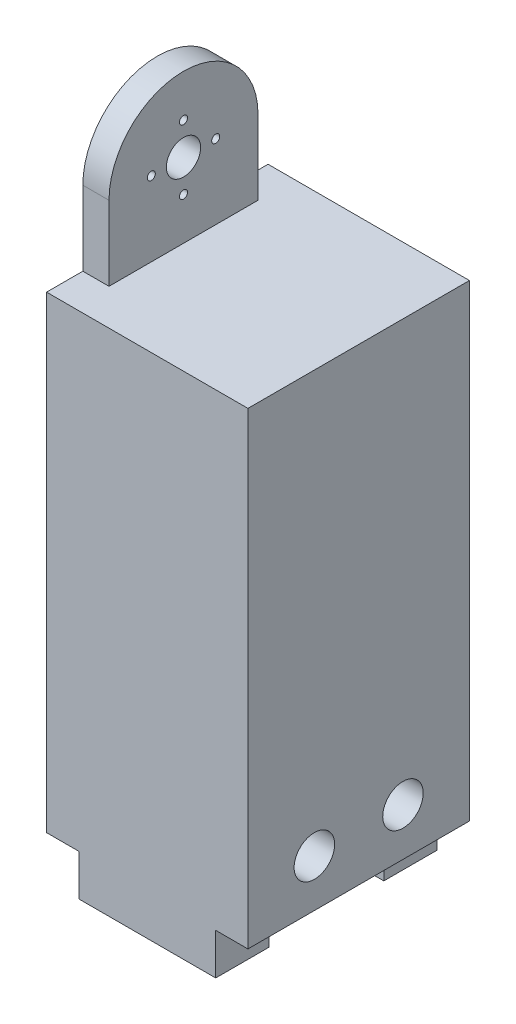
SolidWorks part; units mm, degrees
ref_plane "Front Plane" through (0, 0, 0) normal (0, 0, 1) x (1, 0, 0)
ref_plane "Top Plane" through (0, 0, 0) normal (0, 1, 0) x (1, 0, 0)
ref_plane "Right Plane" through (0, 0, 0) normal (1, 0, 0) x (0, 0, -1)
sketch "Sketch1" plane through (0, 0, 0) normal (0, 0, 1) x (1, 0, 0)
  line L1 (-25, 0) -> (25, 0)
  line L2 (-25, 0) -> (-25, -150)
  line L3 (-25, -150) -> (25, -150)
  line L4 (25, 0) -> (25, -150)
  dimension "D1" = 50
  dimension "D2" = 150
extrude "Boss-Extrude1" add sketch "Sketch1" against normal blind 55
sketch "Sketch2" plane through (25, 0, 0) normal (1, 0, 0) x (0, 0, -1)
  line L0 (55, 0) -> (0, 0) construction
  line L1 (0, -150) -> (0, 0) construction
  circle A0 centre (27.5, -25) radius 10.25
  dimension "D1" = 25
  dimension "D2" = 27.5
extrude "Cut-Extrude1" cut sketch "Sketch2" against normal blind 45 and the other way through all
sketch "Sketch7" plane through (-20, 0, 0) normal (1, 0, 0) x (0, 0, -1)
  line L0 (27.5, -17) -> (27.5, -33) construction
  circle A0 centre (27.5, -25) radius 8
  circle A1 centre (27.5, -17) radius 1
  circle A2 centre (35.5, -25) radius 1
  circle A3 centre (27.5, -33) radius 1
  circle A4 centre (19.5, -25) radius 1
  circle A5 centre (27.5, -25) radius 4.25
  point P14 (27.5, -25)
  dimension "D1" = 16
  dimension "D2" = 2
  dimension "D4" = 8.5
  dimension "D3" = 4
extrude "Cut-Extrude3" cut sketch "Sketch7" against normal blind 10 contours L0 A0 A1 | A0 A1 | A0 L0 A1 | A0 A4 | A0 A4 | L0 A3 A0 | A3 L0 A0 | A0 A3 | A0 A2 | A0 A2 | A5 L0 | L0 A5
sketch "Sketch8" plane through (25, 0, 0) normal (1, 0, 0) x (0, 0, -1)
  line L1 (55, -150) -> (55, 0) construction
  line L3 (0, -150) -> (55, -150)
  line L4 (0, -150) -> (0, -205)
  line L5 (0, -205) -> (55, -205)
  line L6 (55, -150) -> (55, -205)
  circle A1 centre (27.5, -180) radius 10.25
  circle A3 centre (27.5, -25) radius 10.25 construction
  dimension "D1" = 27.5
  dimension "D2" = 155
  dimension "D3" = 25
extrude "Boss-Extrude2" add sketch "Sketch8" against normal blind 50
sketch "Sketch10" plane through (0, 0, 0) normal (0, 0, 1) x (1, 0, 0)
  line L0 (-25, -205) -> (25, -205) construction
  line L5 (17, -205) -> (-17, -205)
  line L6 (17, -205) -> (17, -144.75)
  line L8 (-17, -205) -> (-17, -144.75)
  line L9 (-25, 0) -> (-25, -205) construction
  line L10 (-25, -180) -> (25, -180)
  line L13 (25, -169.75) -> (-25, -169.75)
  line L14 (25, -169.75) -> (25, -190.25)
  line L15 (25, -190.25) -> (-25, -190.25)
  line L16 (-25, -169.75) -> (-25, -190.25)
  line L17 (25, -205) -> (25, 0) construction
  line L18 (0, -180) -> (17, -180)
  line L19 (0, -180) -> (0, -191.25)
  line L20 (0, -191.25) -> (17, -191.25)
  line L21 (17, -180) -> (17, -191.25)
  line L22 (17, -191.25) -> (-17, -191.25)
  line L23 (17, -191.25) -> (17, -169.75)
  line L24 (17, -169.75) -> (-17, -169.75)
  line L25 (-17, -191.25) -> (-17, -169.75)
  line L26 (17, -191.25) -> (-17, -191.25)
  line L27 (17, -191.25) -> (17, -144.75)
  line L28 (17, -144.75) -> (-17, -144.75)
  line L29 (-17, -191.25) -> (-17, -144.75)
  line L30 (-25, -169.75) -> (-17, -169.75)
  line L31 (-25, -169.75) -> (-25, -205)
  line L32 (-25, -205) -> (-17, -205)
  line L33 (-17, -169.75) -> (-17, -205)
  line L34 (25, -169.75) -> (17, -169.75)
  line L35 (25, -169.75) -> (25, -205)
  line L36 (25, -205) -> (17, -205)
  line L37 (17, -169.75) -> (17, -205)
  line L38 (-25, -169.75) -> (25, -169.75)
  line L39 (-25, -169.75) -> (-25, -164.75)
  line L40 (-25, -164.75) -> (25, -164.75)
  line L41 (25, -169.75) -> (25, -164.75)
  line M7 (-25, 0) -> (-25, -205)
  line M8 (-25, -205) -> (25, -205)
  line M9 (25, -205) -> (25, 0)
  dimension "D1" = 8
  dimension "D2" = 8
  dimension "D3" = 11.25
  dimension "D4" = 46.5
  dimension "D5" = 60.25
  dimension "D6" = 5
extrude "Cut-Extrude4" cut sketch "Sketch10" against normal through all contours L20 L22 L8 L6 M8 | L8 L15 M7 M8 | L15 L6 M9 M8 | L15 L8 L10 M7 | L8 L13 L10 M7 | L13 L6 L10 M9 | L15 L10 L6 M9 | L19 L10 L8 L15 | L10 L19 L15 L6 | L6 L13 L8 L10 | L22 L19 L15 L8 | L19 L20 L6 L15 | L29 L40 L27 L28 | L40 L8 L13 L6
sketch "Sketch11" plane through (0, -144.75, 0) normal (0, -1, 0) x (1, 0, 0)
  line L0 (17, -55) -> (17, 0) construction
  line L1 (-17, 0) -> (17, 0)
  line L2 (-17, 0) -> (-17, -13.25)
  line L3 (-17, -13.25) -> (17, -13.25)
  line L4 (17, 0) -> (17, -13.25)
  line L5 (25, -27.5) -> (-30.9131, -27.5) construction
  line L6 (25, -55) -> (25, 0) construction
  line L7 (17, -55) -> (17, -41.75)
  line L8 (-17, -41.75) -> (17, -41.75)
  line L9 (-17, -55) -> (-17, -41.75)
  line L10 (-17, -55) -> (17, -55)
  dimension "D1" = 14.25
extrude "Boss-Extrude4" add sketch "Sketch11" along normal blind 25
sketch "Sketch13" plane through (25, 0, 0) normal (1, 0, 0) x (0, 0, -1)
  line L0 (0, -169.75) -> (0, 0) construction
  line L1 (55, -169.75) -> (0, -169.75)
  line L2 (55, -169.75) -> (55, -159.75)
  line L3 (55, -159.75) -> (0, -159.75)
  line L4 (0, -169.75) -> (0, -159.75)
  dimension "D1" = 10
extrude "Cut-Extrude5" cut sketch "Sketch13" against normal blind 8
ref_plane "Plane2" through (0, 0, 0) normal (1, 0, 0) x (0, 0, -1)
mirror "Mirror2" about plane through (0, 0, 0) normal (1, 0, 0) of "Cut-Extrude5"
sketch "Sketch14" plane through (25, 0, 0) normal (1, 0, 0) x (0, 0, -1)
  line L0 (55, -159.75) -> (0, -159.75) construction
  line L1 (0, -159.75) -> (0, 0) construction
  circle A1 centre (16.5, -148) radius 5.0302
  circle A2 centre (38.5, -148) radius 5.0302
  dimension "D1" = 16.5
  dimension "D2" = 2
  dimension "D3" = 11.75
extrude "Cut-Extrude6" cut sketch "Sketch14" against normal blind 8
mirror "Mirror3" about plane through (0, 0, 0) normal (1, 0, 0) of "Cut-Extrude6"
sketch "Sketch15" plane through (0, 0, 0) normal (0, 0, 1) x (1, 0, 0)
  line L0 (-25, 0) -> (25, 0)
  line L1 (25, 0) -> (0, 0)
  line L3 (-17, -169.75) -> (17, -169.75)
  line L4 (-17, -169.75) -> (-17, -170)
  line L5 (-17, -170) -> (17, -170)
  line L6 (17, -169.75) -> (17, -170)
  line M5 (-17, -169.75) -> (17, -169.75)
  dimension "D1" = 0.25
extrude "Boss-Extrude5" add sketch "Sketch15" against normal blind 13.25 contours L6 L4 L5 M5
ref_plane "Plane3" through (0, 0, -27.5) normal (0, 0, 1) x (1, 0, 0)
mirror "Mirror4" about plane through (0, 0, -27.5) normal (0, 0, 1) of "Boss-Extrude5"
sketch "Sketch16" plane through (0, 0, 0) normal (0, 0, 1) x (1, 0, 0)
  line L7 (-20, -14.75) -> (-18.5, -14.75)
  line L8 (-20, -14.75) -> (-20, -35.25)
  line L9 (-20, -35.25) -> (-18.5, -35.25)
  line L10 (-18.5, -14.75) -> (-18.5, -35.25)
  line L11 (25, 0) -> (-18.5, 0)
  line L12 (25, 0) -> (25, -43.5)
  line L13 (25, -43.5) -> (-18.5, -43.5)
  line L14 (-18.5, 0) -> (-18.5, -43.5)
  line M12 (25, -159.75) -> (25, 0)
  line M13 (25, 0) -> (-25, 0)
  dimension "D1" = 1.5
  dimension "D2" = 43.5
  dimension "D3" = 43.5
extrude "Cut-Extrude7" cut sketch "Sketch16" against normal through all contours L14 L10 L13 M13 M12
sketch "Sketch19" plane through (-20, 0, 0) normal (1, 0, 0) x (0, 0, -1)
  circle A0 centre (27.5, -25) radius 4.25
  circle A1 centre (35.5, -25) radius 1
  circle A2 centre (27.5, -33) radius 1
  circle A3 centre (19.5, -25) radius 1
  circle A4 centre (27.5, -17) radius 1
  point P15 (27.5, -25)
  circle M5 centre (27.5, -25) radius 4.25
  circle M6 centre (27.5, -17) radius 1
  circle M7 centre (35.5, -25) radius 1
  circle M8 centre (27.5, -33) radius 1
  circle M9 centre (19.5, -25) radius 1
  circle M10 centre (27.5, -25) radius 10.25
  dimension "D1" = 4
extrude "Boss-Extrude6" add sketch "Sketch19" along normal blind 1.5 contours M10 M6 M8 M9 M7 M5
sketch "Sketch20" plane through (-18.5, 0, 0) normal (1, 0, 0) x (0, 0, -1)
  line L0 (0, -43.5) -> (9, -43.5)
  line L1 (9, -25) -> (9, -43.5)
  line L2 (9, -43.5) -> (0, -43.5)
  line L3 (46, -25) -> (46, -43.5)
  line L4 (46, -43.5) -> (55, -43.5)
  line L5 (46, -43.5) -> (55, -43.5)
  line L7 (9, -43.5) -> (0, -43.5)
  line L8 (9, -43.5) -> (9, -25)
  line L12 (9, -25) -> (9, -43.5)
  line L13 (9, -43.5) -> (0, -43.5)
  line L15 (0, 0) -> (55, 0)
  line L16 (0, 0) -> (0, -43.5)
  line L17 (0, -43.5) -> (55, -43.5)
  line L18 (55, 0) -> (55, -43.5)
  circle A0 centre (27.5, -25) radius 18.5
  line M6 (0, 0) -> (0, -43.5)
  line M7 (0, -43.5) -> (55, -43.5)
  line M8 (55, -43.5) -> (55, 0)
  line M9 (55, 0) -> (0, 0)
extrude "Cut-Extrude8" cut sketch "Sketch20" against normal through all contours A0 L3 L1 M7 M8 M9 M6
